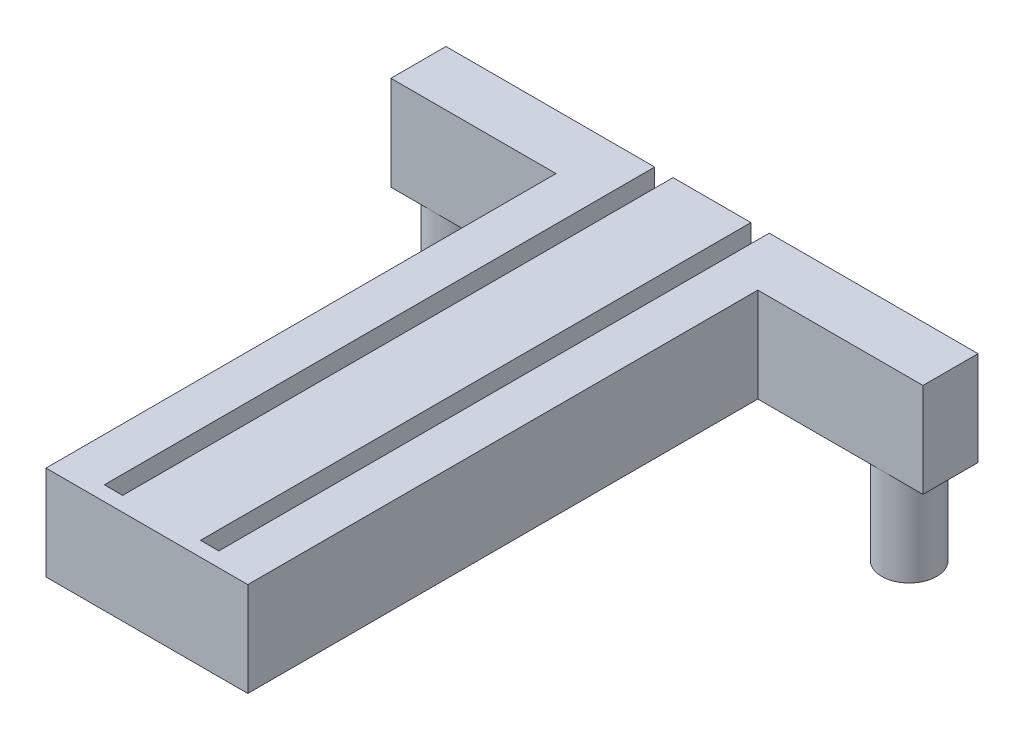
SolidWorks part; units mm, degrees
ref_plane "Front Plane" through (0, 0, 0) normal (0, 0, 1) x (1, 0, 0)
ref_plane "Top Plane" through (0, 0, 0) normal (0, 1, 0) x (1, 0, 0)
ref_plane "Right Plane" through (0, 0, 0) normal (1, 0, 0) x (0, 0, -1)
sketch "Sketch2" plane through (0, 0, 0) normal (0, 0, 1) x (1, 0, 0)
  line L0 (-1.7961, 1.7961) -> (-5.3882, 5.3882)
  line L1 (-5.3882, 5.3882) -> (-5.3882, 10.4682)
  line L2 (1.7961, 1.7961) -> (5.3882, 5.3882)
  line L3 (5.3882, 5.3882) -> (5.3882, 10.4682)
  line L4 (5.3882, 10.4682) -> (-5.3882, 10.4682)
  line L5 (1.7961, 0) -> (5.3882, 0)
  line L6 (5.3882, 0) -> (7.9282, 0)
  line L7 (7.9282, 0) -> (7.9282, 10.4682)
  line L8 (-7.9282, 10.4682) -> (-19.3582, 10.4682)
  line L9 (-7.9282, 10.4682) -> (-7.9282, 0)
  line L10 (-7.9282, 0) -> (-1.7961, 0)
  line L11 (1.7961, 1.7961) -> (1.7961, 0)
  line L12 (7.9282, 10.4682) -> (19.3582, 10.4682)
  line L13 (-1.7961, 1.7961) -> (-1.7961, 0)
  line L17 (31.75, 10.4682) -> (19.3582, 10.4682)
  line L21 (-31.75, 10.4682) -> (-19.3582, 10.4682)
  line L23 (31.75, -2.5915) -> (-31.75, -2.5915)
  line L27 (-36.83, 10.4682) -> (-36.83, -2.5915)
  line L28 (-36.83, -2.5915) -> (-31.75, -2.5915)
  line L31 (36.83, -2.5915) -> (36.83, 10.4682)
  line L32 (36.83, 10.4682) -> (31.75, 10.4682)
  line L33 (31.75, -2.5915) -> (36.83, -2.5915)
  line L34 (-31.75, 10.4682) -> (-36.83, 10.4682)
extrude "Boss-Extrude1" add sketch "Sketch2" along normal blind 76.2
sketch "Sketch3" plane through (0, 10.4682, 0) normal (0, 1, 0) x (1, 0, 0)
  line L1 (-36.83, -76.2) -> (-13.97, -76.2)
  line L2 (-36.83, -76.2) -> (-36.83, -7.62)
  line L3 (-36.83, -7.62) -> (-13.97, -7.62)
  line L4 (-13.97, -76.2) -> (-13.97, -7.62)
  line L5 (-36.83, -76.2) -> (-13.97, -7.62) construction
  line L6 (-36.83, -7.62) -> (-13.97, -76.2) construction
  line L7 (36.83, -76.2) -> (13.97, -76.2)
  line L8 (36.83, -76.2) -> (36.83, -7.62)
  line L9 (36.83, -7.62) -> (13.97, -7.62)
  line L10 (13.97, -76.2) -> (13.97, -7.62)
  line L11 (36.83, -76.2) -> (13.97, -7.62) construction
  line L12 (36.83, -7.62) -> (13.97, -76.2) construction
  point P4 (-25.4, -41.91)
  point P10 (25.4, -41.91)
extrude "Cut-Extrude1" cut sketch "Sketch3" against normal blind 76.2
sketch "Sketch4" plane through (0, 0, 76.2) normal (0, 0, 1) x (1, 0, 0)
  line L1 (-13.97, 10.4682) -> (13.97, 10.4682)
  line L2 (-13.97, 10.4682) -> (-13.97, -2.5915)
  line L3 (-13.97, -2.5915) -> (13.97, -2.5915)
  line L4 (13.97, 10.4682) -> (13.97, -2.5915)
  line L5 (-13.97, 10.4682) -> (13.97, -2.5915) construction
  line L6 (-13.97, -2.5915) -> (13.97, 10.4682) construction
  point P4 (0, 3.9383)
extrude "Boss-Extrude2" add sketch "Sketch4" along normal blind 0.762
sketch "Sketch5" plane through (0, 0, 76.962) normal (0, 0, 1) x (1, 0, 0)
  line L0 (1.329, -2.5915) -> (1.329, 0.7141)
  line L1 (-13.97, -2.5915) -> (13.97, -2.5915) construction
  line L2 (1.329, 1.4926) -> (2.8507, 1.4926)
  line L3 (2.8507, 1.4926) -> (2.8507, 0.7141)
  line L4 (2.8507, 0.7141) -> (1.329, 0.7141)
  line L5 (0, 0.7141) -> (0, -2.5915)
  line L6 (1.329, 1.4926) -> (0, 1.4926)
  line L7 (0, 1.4926) -> (0, 0.7141)
  line L8 (0, -2.5915) -> (1.329, -2.5915)
extrude "Cut-Extrude2" cut sketch "Sketch5" against normal blind 99.822
sketch "Sketch7" plane through (0, 0, 76.962) normal (0, 0, 1) x (1, 0, 0)
  line L1 (-13.97, 10.4682) -> (13.97, 10.4682)
  line L2 (-13.97, 10.4682) -> (-13.97, -2.5915)
  line L3 (-13.97, -2.5915) -> (13.97, -2.5915)
  line L4 (13.97, 10.4682) -> (13.97, -2.5915)
  line L5 (-13.97, 10.4682) -> (13.97, -2.5915) construction
  line L6 (-13.97, -2.5915) -> (13.97, 10.4682) construction
  point P4 (0, 3.9383)
extrude "Boss-Extrude3" add sketch "Sketch7" along normal blind 1.27
sketch "Sketch8" plane through (0, -2.5915, 0) normal (0, -1, 0) x (1, 0, 0)
  line L0 (-36.83, 7.62) -> (-25.4, 7.62) construction
  line L1 (-13.97, 7.62) -> (-36.83, 7.62) construction
  line L2 (36.83, 7.62) -> (25.4, 7.62) construction
  line L3 (36.83, 7.62) -> (13.97, 7.62) construction
  circle A0 centre (-31.115, 3.81) radius 3.81
  circle A1 centre (31.115, 3.81) radius 3.81
extrude "Boss-Extrude4" add sketch "Sketch8" along normal blind 12.7
ref_plane "Plane1" through (-46.83, 0, 0) normal (-1, 0, 0) x (0, 0, 1)
sketch "Sketch10" plane through (-46.83, 0, 0) normal (-1, 0, 0) x (0, 0, 1)
  line L0 (0, -12.3341) -> (0, -6.0921)
  line L1 (0, -2.5915) -> (0, -15.2915) construction
  line L2 (0, -6.0921) -> (1.212, -6.0921)
  line L3 (1.212, -6.0921) -> (1.212, -12.3341)
  line L4 (1.212, -12.3341) -> (0, -12.3341)
extrude "Cut-Extrude3" cut sketch "Sketch10" against normal through all both and the other way through all
